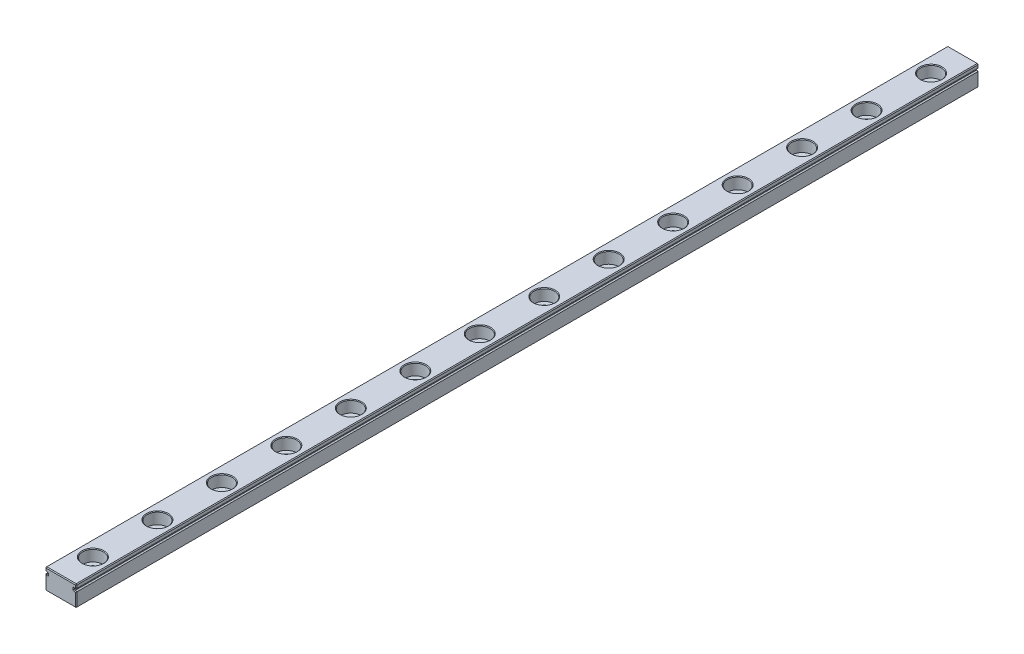
SolidWorks part; units mm, degrees
material "AISI 304"
ref_plane "Front Plane" through (0, 0, 0) normal (0, 0, 1) x (1, 0, 0)
ref_plane "Top Plane" through (0, 0, 0) normal (0, 1, 0) x (1, 0, 0)
ref_plane "Right Plane" through (0, 0, 0) normal (1, 0, 0) x (0, 0, -1)
sketch "Sketch1" plane through (0, 0, 0) normal (0, 0, 1) x (1, 0, 0)
  line L0 (0, 0) -> (0, 8) construction
  line L1 (0, 8) -> (12, 8)
  line L2 (0, 0) -> (12, 0)
  line L3 (0, 8) -> (0, 6.75)
  line L4 (0, 6.75) -> (0.5, 6.25) construction
  line L5 (0.5, 6.25) -> (1, 6.25)
  line L6 (0.5, 5.75) -> (0, 5.25) construction
  line L7 (0, 5.25) -> (0, 0)
  line L8 (1, 6.25) -> (1, 5.75)
  line L9 (1, 5.75) -> (0.5, 5.75)
  line L10 (0.5, 5.75) -> (0.75, 6) construction
  line L11 (0.75, 6) -> (0.5, 6.25) construction
  line L12 (0, 6.75) -> (0, 6.559)
  line L13 (0, 5.25) -> (0, 5.441)
  line L14 (6, 8) -> (6, 0) construction
  line L15 (11.25, 6) -> (11.5, 6.25) construction
  line L16 (11.5, 5.75) -> (11.25, 6) construction
  line L17 (11.5, 5.75) -> (12, 5.25) construction
  line L18 (12, 6.75) -> (11.5, 6.25) construction
  line L19 (12, 0) -> (12, 8) construction
  line L20 (12, 5.25) -> (12, 5.441)
  line L21 (12, 6.75) -> (12, 6.559)
  line L22 (11, 5.75) -> (11.5, 5.75)
  line L23 (11, 6.25) -> (11, 5.75)
  line L24 (12, 5.25) -> (12, 0)
  line L25 (11.5, 6.25) -> (11, 6.25)
  line L26 (12, 8) -> (12, 6.75)
  arc A0 (0, 5.441) -> (0.5, 5.75) centre (0, 6) ccw
  arc A1 (0.5, 6.25) -> (0, 6.559) centre (0, 6) ccw
  arc A2 (11.5, 6.25) -> (12, 6.559) centre (12, 6) cw
  arc A3 (12, 5.441) -> (11.5, 5.75) centre (12, 6) cw
  point P4 (1, 6)
  point P28 (11, 6)
  dimension "D1" = 8
  dimension "D2" = 6
  dimension "D3" = 0.5
  dimension "D4" = 45
  dimension "D5" = 2
  dimension "D6" = 1
extrude "Boss-Extrude1" add sketch "Sketch1" along normal blind 350
chamfer "Chamfer1" distance 0.3 angle 45 36 edges at (0, 0, 175) (12, 0, 175) (0, 8, 175) (12, 8, 175) (0.2939, 5.5245, 350) (0.75, 5.75, 350) (1, 6, 350) (0.75, 6.25, 350) (0.2939, 6.4755, 350) (0, 7.2795, 350) (6, 8, 350) (12, 7.2795, 350) (11.7061, 6.4755, 350) (11.25, 6.25, 350) (11, 6, 350) (11.25, 5.75, 350) (11.7061, 5.5245, 350) (12, 2.7205, 350) (6, 0, 350) (0, 2.7205, 350) (12, 2.7205, 0) (11.7061, 5.5245, 0) (11.25, 5.75, 0) (11, 6, 0) (11.25, 6.25, 0) (11.7061, 6.4755, 0) (12, 7.2795, 0) (6, 0, 0) (0, 2.7205, 0) (0.2939, 5.5245, 0) (0.75, 5.75, 0) (1, 6, 0) (0.75, 6.25, 0) (0.2939, 6.4755, 0) (0, 7.2795, 0) (6, 8, 0)
hole_wizard "CBORE for M5 Hex Head Bolt1" positions "3DSketch1" profile "Sketch3" counterbore size "M5" standard "ANSI Metric" end condition through all
sketch3d "3DSketch1"
  line L0 (6, 8, 0) -> (6, 8, 12.5) construction
  line L1 (11.7, 8, 0) -> (0.3, 8, 0) construction
  point P0 (6, 8, 12.5)
  dimension "D1" = 12.5
sketch "Sketch3" plane through (6, 8, 12.5) normal (1, 0, 0) x (0, 0, 1)
  line L0 (0, 0) -> (0, 8)
  line L1 (2.25, 7.75) -> (2.5, 8)
  line L2 (4, 4.5) -> (2.25, 4.5)
  line L3 (2.25, 4.5) -> (2.25, 7.75)
  line L5 (4, 4.5) -> (4, 0.25)
  line L6 (4, 0.25) -> (4.25, 0)
  line L7 (4.25, 0) -> (0, 0)
  line L8 (-4, 0.25) -> (-4.25, 0) construction
  line L11 (0, -6.35) -> (0, 107.95) construction
  line L12 (2.5, 8) -> (0, 8)
  line L13 (-2.25, 7.75) -> (-2.5, 8) construction
  dimension "Thru Hole Dia." = 4.5
  dimension "Thru Hole Depth" = 8
  dimension "C'Bore Dia." = 8
  dimension "C'Bore Depth" = 4.5
  dimension "Near C'Sink Dia." = 8.5
  dimension "Near C'Sink Angle" = 90
  dimension "Far C'Sink Dia." = 5
  dimension "Far C'Sink Angle" = 90
pattern_linear "LPattern1" count 14 spacing 25 along (0, 0, 1) of "CBORE for M5 Hex Head Bolt1"
